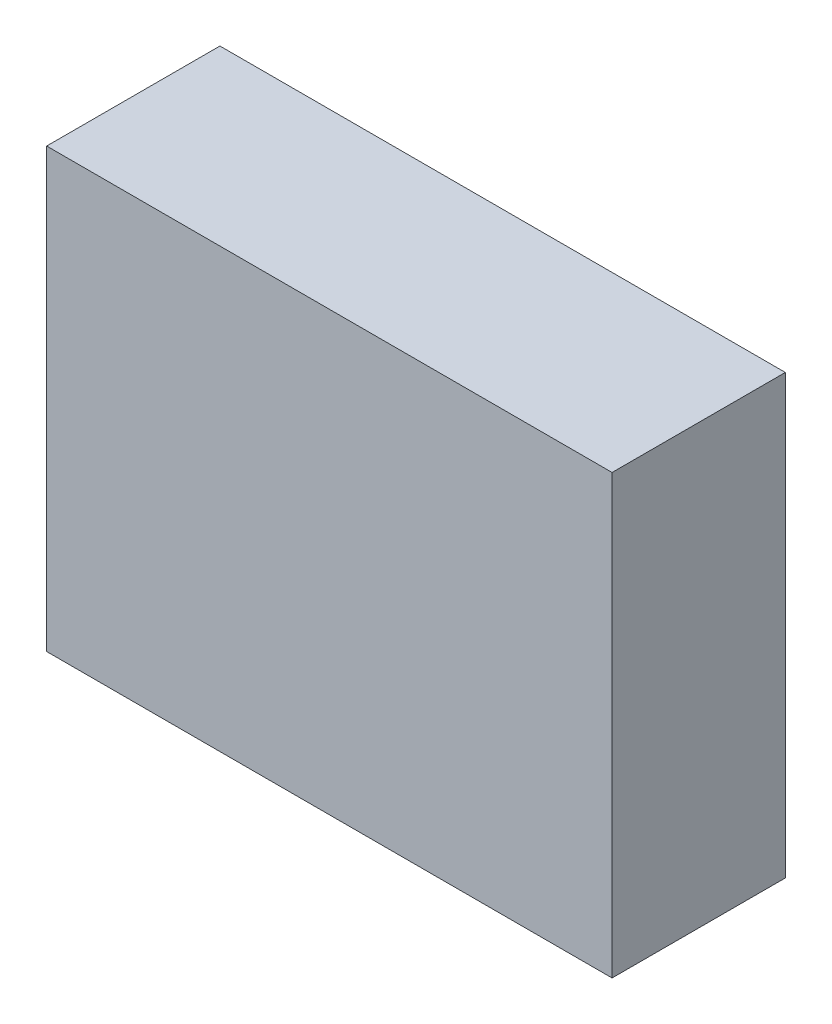
SolidWorks part; units mm, degrees
ref_plane "Front Plane" through (0, 0, 0) normal (0, 0, 1) x (1, 0, 0)
ref_plane "Top Plane" through (0, 0, 0) normal (0, 1, 0) x (1, 0, 0)
ref_plane "Right Plane" through (0, 0, 0) normal (1, 0, 0) x (0, 0, -1)
sketch "Sketch1" plane through (0, 0, 0) normal (0, 0, 1) x (1, 0, 0)
  line L0 (-1.6635, 1.2635) -> (1.6, 1.2635)
  line L1 (1.6, 1.2635) -> (1.6, -1.2635)
  line L2 (1.6, -1.2635) -> (-1.6635, -1.2635)
  line L3 (-1.6635, -1.2635) -> (-1.6635, 1.2635)
extrude "Component_Outline" add sketch "Sketch1" along normal blind 1 separate body
sketch3d "3DSketch1"
  line L0 (0, 0, 0) -> (1, 0, 0)
  line L1 (0, 0, 0) -> (0, 1, 0)
  line L2 (0, 0, 0) -> (0, 0, 1)
  point P0 (0, 0, 0)
